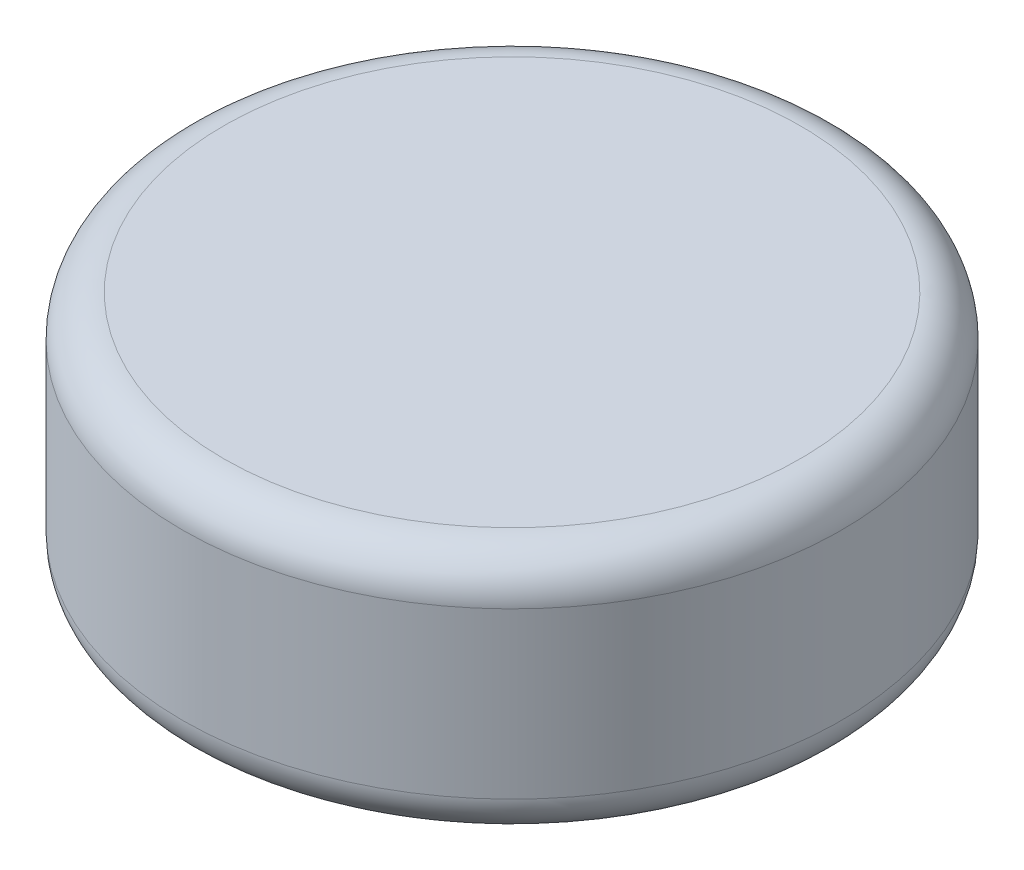
SolidWorks part; units mm, degrees
ref_plane "Front Plane" through (0, 0, 0) normal (0, 0, 1) x (1, 0, 0)
ref_plane "Top Plane" through (0, 0, 0) normal (0, 1, 0) x (1, 0, 0)
ref_plane "Right Plane" through (0, 0, 0) normal (1, 0, 0) x (0, 0, -1)
sketch "Sketch1" plane through (0, 0, 0) normal (0, 1, 0) x (1, 0, 0)
  circle A0 centre (0, 0) radius 2
  dimension "D1" = 4
extrude "Boss-Extrude1" add sketch "Sketch1" along normal blind 1.5
fillet "Fillet1" radius 0.25 2 edges at (0, 0, 2) (0, 1.5, 2)
